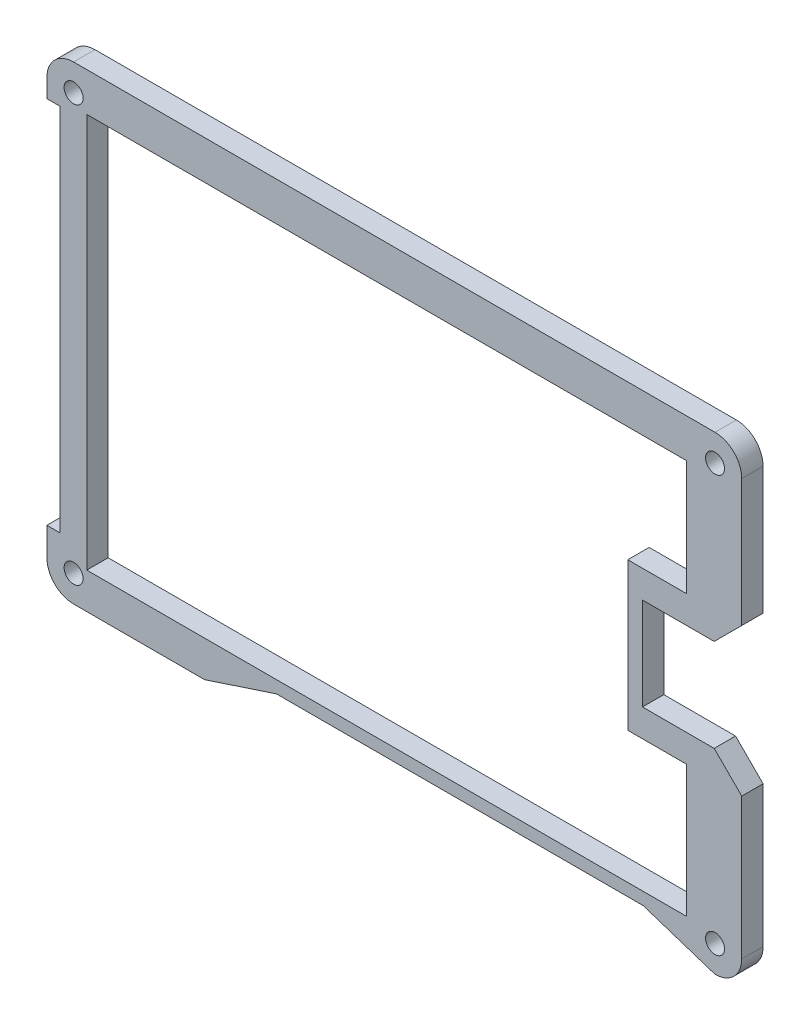
SolidWorks part; units mm, degrees
ref_plane "Front Plane" through (0, 0, 0) normal (0, 0, 1) x (1, 0, 0)
ref_plane "Top Plane" through (0, 0, 0) normal (0, 1, 0) x (1, 0, 0)
ref_plane "Right Plane" through (0, 0, 0) normal (1, 0, 0) x (0, 0, -1)
sketch "Sketch1" plane through (0, 0, 0) normal (0, 0, 1) x (1, 0, 0)
  line L0 (-309.8086, 128.8851) -> (-305.8779, 128.8851) construction
  line L1 (-305.8779, 128.8851) -> (-301.9473, 132.8157) construction
  line L2 (-301.9473, 132.8157) -> (-301.9473, 150.9704) construction
  line L3 (-305.7573, 154.7804) -> (-397.2471, 154.7804) construction
  line L4 (-401.0571, 150.9566) -> (-401.0571, 148.341) construction
  line L5 (-401.0571, 148.341) -> (-399.1521, 148.341) construction
  line L6 (-399.1521, 148.341) -> (-399.1521, 95.6449) construction
  line L7 (-399.1521, 95.6449) -> (-401.0571, 95.6449) construction
  line L8 (-401.0571, 95.6449) -> (-401.0571, 91.6593) construction
  line L9 (-378.5565, 87.8217) -> (-397.2472, 87.8217) construction
  line L10 (-368.3165, 91.1883) -> (-378.5565, 87.8217) construction
  line L11 (-315.9973, 91.1883) -> (-368.3165, 91.1883) construction
  line L12 (-315.9973, 91.1883) -> (-305.7573, 87.8217) construction
  line L13 (-301.9473, 91.6317) -> (-301.9473, 111.7465) construction
  line L14 (-305.8779, 115.6771) -> (-301.9473, 111.7465) construction
  line L15 (-309.8086, 115.6771) -> (-305.8779, 115.6771) construction
  line L16 (-309.8086, 128.8851) -> (-305.8779, 128.8851)
  line L17 (-305.8779, 128.8851) -> (-301.9473, 132.8157)
  line L18 (-301.9473, 132.8157) -> (-301.9473, 150.9704)
  line L19 (-305.7573, 154.7804) -> (-397.2471, 154.7804)
  line L20 (-401.0571, 150.9566) -> (-401.0571, 148.341)
  line L21 (-401.0571, 148.341) -> (-399.1521, 148.341)
  line L22 (-399.1521, 148.341) -> (-399.1521, 95.6449)
  line L23 (-399.1521, 95.6449) -> (-401.0571, 95.6449)
  line L24 (-401.0571, 95.6449) -> (-401.0571, 91.6593)
  line L25 (-378.5565, 87.8217) -> (-397.2472, 87.8217)
  line L26 (-368.3165, 91.1883) -> (-378.5565, 87.8217)
  line L27 (-315.9973, 91.1883) -> (-368.3165, 91.1883)
  line L28 (-315.9973, 91.1883) -> (-305.7573, 87.8217)
  line L29 (-301.9473, 91.6317) -> (-301.9473, 111.7465)
  line L30 (-305.8779, 115.6771) -> (-301.9473, 111.7465)
  line L31 (-309.8086, 115.6771) -> (-305.8779, 115.6771)
  line L32 (-309.8086, 128.8851) -> (-316.1078, 128.8851)
  line L33 (-316.1078, 128.8851) -> (-316.1078, 115.6771)
  line L34 (-316.1078, 115.6771) -> (-309.8086, 115.6771)
  line L35 (-395.3675, 92.9525) -> (-395.3675, 149.2432) construction
  line L36 (-395.3675, 92.9525) -> (-395.3675, 149.2432)
  line L37 (-395.3675, 149.2432) -> (-309.8086, 149.2432) construction
  line L38 (-395.3675, 149.2432) -> (-309.8086, 149.2432)
  line L39 (-395.3675, 92.9525) -> (-309.8086, 92.9525) construction
  line L40 (-395.3675, 92.9525) -> (-309.8086, 92.9525)
  line L41 (-309.8086, 111.7465) -> (-318.2033, 111.7465)
  line L42 (-309.8086, 115.6771) -> (-309.8086, 92.9525) construction
  line L43 (-318.2033, 111.7465) -> (-318.2033, 132.8157)
  line L44 (-318.2033, 134.8668) -> (-318.2033, 116.6297) construction
  line L45 (-318.2033, 132.8157) -> (-309.8086, 132.8157)
  line L46 (-309.8086, 149.2432) -> (-309.8086, 128.8851) construction
  line L47 (-309.8086, 132.8157) -> (-309.8086, 149.2432)
  line L48 (-309.8086, 111.7465) -> (-309.8086, 92.9525)
  arc A0 (-301.9473, 150.9704) -> (-305.7573, 154.7804) centre (-305.7573, 150.9704) ccw construction
  arc A1 (-397.2471, 154.7804) -> (-401.0571, 150.9566) centre (-397.2471, 150.9704) ccw construction
  arc A2 (-401.0571, 91.6593) -> (-397.2472, 87.8217) centre (-397.2472, 91.6317) ccw construction
  arc A3 (-305.7573, 87.8217) -> (-301.9473, 91.6317) centre (-305.7573, 91.6317) ccw construction
  arc A4 (-301.9473, 150.9704) -> (-305.7573, 154.7804) centre (-305.7573, 150.9704) ccw
  arc A5 (-397.2471, 154.7804) -> (-401.0571, 150.9566) centre (-397.2471, 150.9704) ccw
  arc A6 (-401.0571, 91.6593) -> (-397.2472, 87.8217) centre (-397.2472, 91.6317) ccw
  arc A7 (-305.7573, 87.8217) -> (-301.9473, 91.6317) centre (-305.7573, 91.6317) ccw
  dimension "D1" = 6.2992
extrude "Boss-Extrude1" add sketch "Sketch1" along normal blind 3.048
sketch "Sketch2" plane through (0, 0, 0) normal (0, 0, -1) x (-1, 0, 0)
  circle A0 centre (305.7573, 150.9704) radius 1.3559
  circle A1 centre (397.2471, 150.9704) radius 1.3559
  circle A2 centre (397.2472, 91.6317) radius 1.3559
  circle A3 centre (305.7573, 91.6317) radius 1.3559
  dimension "D1" = 2.7118
extrude "Cut-Extrude1" cut sketch "Sketch2" against normal through all
